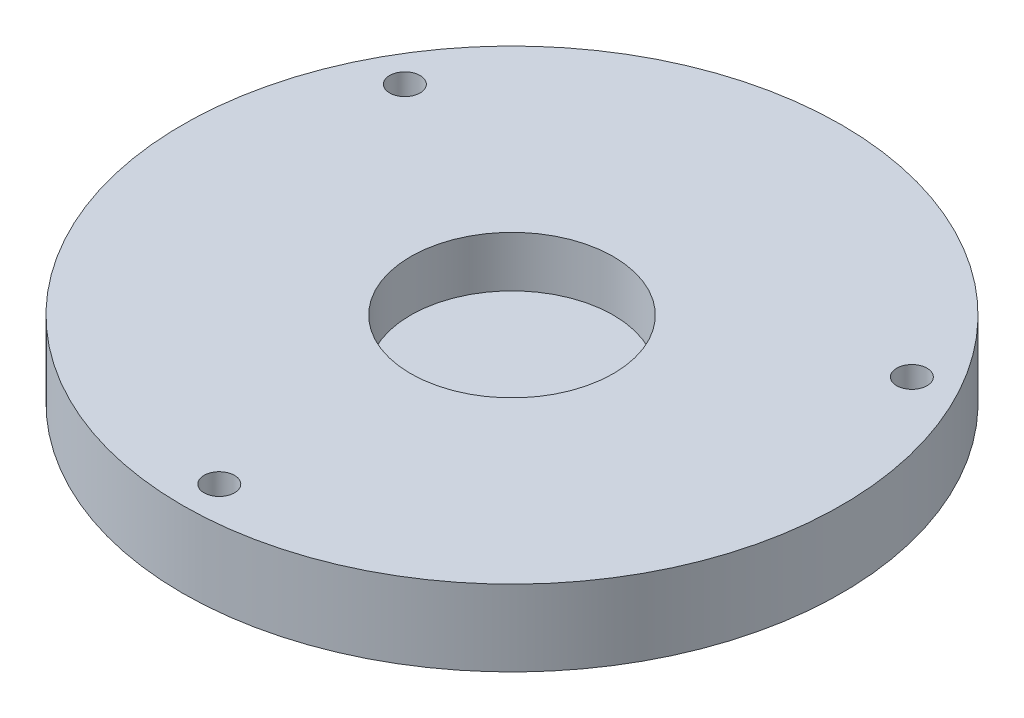
SolidWorks part; units mm, degrees
ref_plane "Спереди" through (0, 0, 0) normal (0, 0, 1) x (1, 0, 0)
ref_plane "Сверху" through (0, 0, 0) normal (0, 1, 0) x (1, 0, 0)
ref_plane "Справа" through (0, 0, 0) normal (1, 0, 0) x (0, 0, -1)
sketch "Эскиз2" plane through (0, 0, 0) normal (0, 1, 0) x (1, 0, 0)
  circle A0 centre (0, 0) radius 65
extrude "Бобышка-Вытянуть1" add sketch "Эскиз2" along normal blind 15 contours A0
sketch "Эскиз5" plane through (0, 15, 0) normal (0, 1, 0) x (1, 0, 0)
  line L0 (21.5923, 61.3088) -> (-23.7511, -67.4386) construction
  line L1 (-62.6325, 17.3829) -> (57.2195, -15.8806) construction
  circle A0 centre (0, 0) radius 65 construction
  circle A1 centre (0, 0) radius 20
extrude "Вырез-Вытянуть1" cut sketch "Эскиз5" against normal blind 10
sketch "Эскиз6" plane through (0, 0, 0) normal (0, -1, 0) x (1, 0, 0)
  line L0 (0, 65) -> (0, -65) construction
  line L1 (-65, 0) -> (65, 0) construction
  line L3 (0, 57.735) -> (-50, -28.8675)
  line L4 (-50, -28.8675) -> (50, -28.8675)
  line L5 (50, -28.8675) -> (0, 57.735)
  circle A0 centre (0, 0) radius 65 construction
  circle A1 centre (0, 0) radius 28.8675 construction
  circle A2 centre (0, 57.735) radius 3
  circle A3 centre (-50, -28.8675) radius 3
  circle A4 centre (50, -28.8675) radius 3
  dimension "D1" = 100
extrude "Вырез-Вытянуть2" cut sketch "Эскиз6" against normal blind 15 contours A2 | A3 | A4
